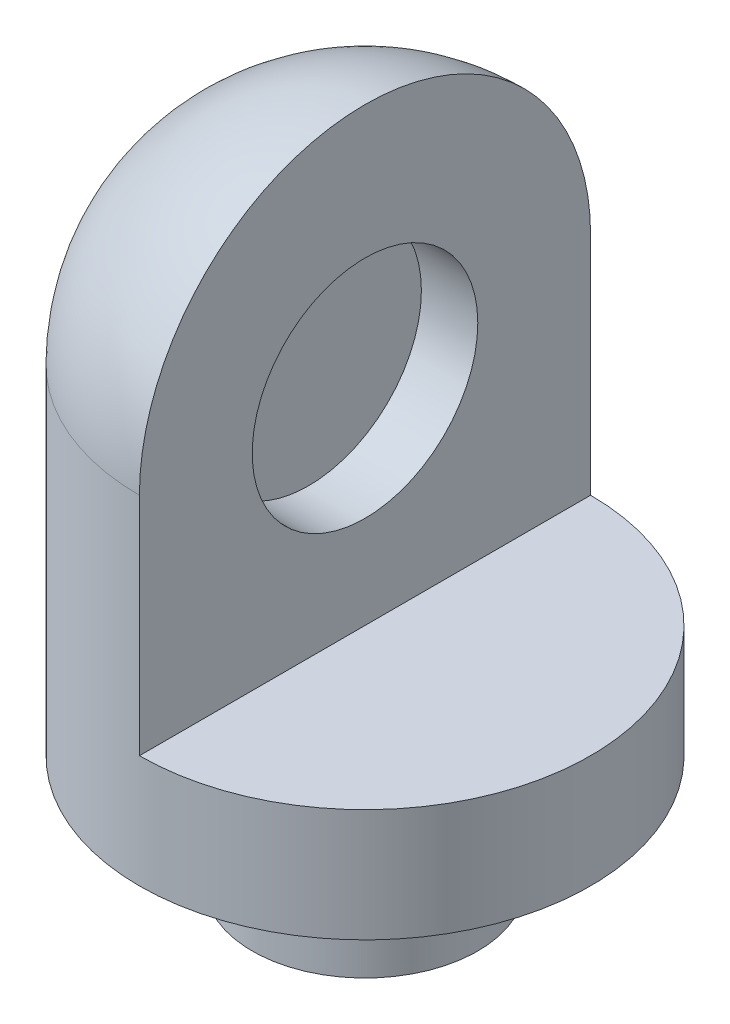
SolidWorks part; units mm, degrees
ref_plane "Front Plane" through (0, 0, 0) normal (0, 0, 1) x (1, 0, 0)
ref_plane "Top Plane" through (0, 0, 0) normal (0, 1, 0) x (1, 0, 0)
ref_plane "Right Plane" through (0, 0, 0) normal (1, 0, 0) x (0, 0, -1)
sketch "Sketch1" plane through (0, 0, 0) normal (0, 1, 0) x (1, 0, 0)
  circle A0 centre (0, 0) radius 40
extrude "Boss-Extrude1" add sketch "Sketch1" along normal blind 100
sketch "Sketch2" plane through (0, 0, 0) normal (0, -1, 0) x (1, 0, 0)
  circle A0 centre (0, 0) radius 20
extrude "Boss-Extrude2" add sketch "Sketch2" along normal blind 20
sketch "Sketch3" plane through (0, 100, 0) normal (0, 1, 0) x (1, 0, 0)
  line L0 (0, 40) -> (0, -40)
  line L1 (0, 40) -> (41.3043, 40)
  line L2 (0, -40) -> (41.3043, -40)
  line L3 (41.3043, 40) -> (41.3043, -40)
  circle A0 centre (0, 0) radius 40 construction
fillet "Fillet2" radius 40 1 edges at (0, 100, 40)
extrude "Cut-Extrude5" cut sketch "Sketch3" against normal blind 80 contours L2 L3 L1 L0
sketch "Sketch5" plane through (0, 0, 0) normal (1, 0, 0) x (0, 0, -1)
  circle A0 centre (0, 56.4426) radius 20
extrude "Cut-Extrude6" cut sketch "Sketch5" against normal blind 10
